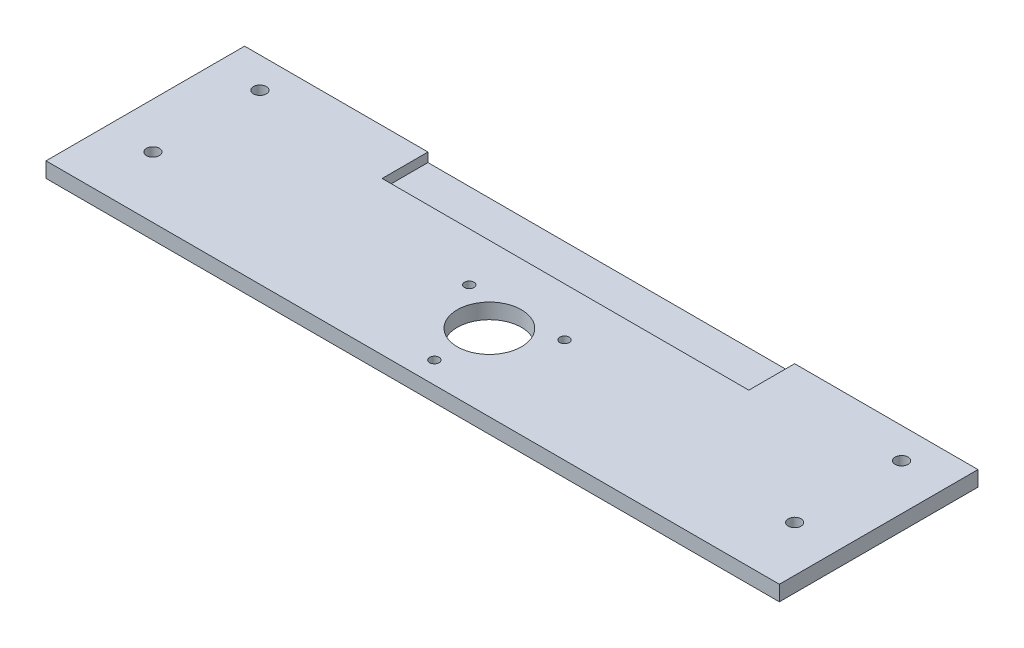
SolidWorks part; units mm, degrees
material "Thornel Mat VMA"
ref_plane "前视基准面" through (0, 0, 0) normal (0, 0, 1) x (1, 0, 0)
ref_plane "上视基准面" through (0, 0, 0) normal (0, 1, 0) x (1, 0, 0)
ref_plane "右视基准面" through (0, 0, 0) normal (1, 0, 0) x (0, 0, -1)
sketch "草图1" plane through (0, 0, 0) normal (0, 1, 0) x (1, 0, 0)
  line L0 (-105, 57.5) -> (-105, -7.5) construction
  line L1 (-120, -7.5) -> (120, -7.5)
  line L2 (-120, -7.5) -> (-120, 57.5)
  line L3 (-120, 57.5) -> (120, 57.5)
  line L4 (120, -7.5) -> (120, 57.5)
  line L5 (-120, -7.5) -> (120, 57.5) construction
  line L6 (-120, 57.5) -> (120, -7.5) construction
  line L7 (0, 57.5) -> (0, -7.5) construction
  line L8 (0, -57.5) -> (0, -7.5) construction
  line L9 (-60, -7.5) -> (20, -7.5)
  circle A0 centre (-105, 47.5) radius 2.1
  circle A1 centre (-105, 12.5) radius 2.1
  circle A2 centre (105, 12.5) radius 2.1
  circle A3 centre (105, 47.5) radius 2.1
  point P0 (0, 25)
  dimension "D1" = 65
  dimension "D2" = 240
  dimension "D3" = 15
  dimension "D4" = 35
  dimension "D5" = 20
extrude "凸台-拉伸1" add sketch "草图1" along normal blind 5 contours L1 L4 L3 L2 A2 A1 A0 A3
sketch "草图2" plane through (0, 5, 0) normal (0, 1, 0) x (1, 0, 0)
  line L0 (0, 57.5) -> (0, -7.5) construction
  line L1 (-120, 57.5) -> (120, 57.5) construction
  line L2 (-120, -7.5) -> (120, -7.5) construction
  line L3 (-60, 57.5) -> (-60, 42.5)
  line L4 (-60, 42.5) -> (60, 42.5)
  line L5 (60, 57.5) -> (60, 42.5)
  line L6 (-60, 57.5) -> (60, 57.5)
  point P10 (0, 42.5)
  dimension "D1" = 15
  dimension "D2" = 60
extrude "切除-拉伸1" cut sketch "草图2" against normal blind 3
fillet "圆角1" [suppressed] radius 5
sketch "草图3" plane through (0, 5, 0) normal (0, 1, 0) x (1, 0, 0)
  line L0 (-55, 42.5) -> (55, 42.5) construction
  line L1 (-55, 42.5) -> (55, 42.5)
  line L2 (0, 42.5) -> (0, -7.3132) construction
  circle A0 centre (0, 17.5934) radius 10.5
  circle A1 centre (0, -0.4066) radius 1.55
  circle A2 centre (-15.5885, 26.5934) radius 1.55
  circle A3 centre (15.5885, 26.5934) radius 1.55
  point P16 (0, 17.5934)
  dimension "D1" = 3
extrude "切除-拉伸2" cut sketch "草图3" against normal blind 32 contours L2 A0 | A0 L2 | A3 | L2 A1 | A1 L2 | A2
sketch "草图4" plane through (0, 5, 0) normal (0, 1, 0) x (1, 0, 0)
  line L0 (22.5, 17.5934) -> (-22.5, 17.5934) construction
  circle A0 centre (0, 17.5934) radius 10.5 construction
  circle A1 centre (0, 17.5934) radius 10.5 construction
  circle A2 centre (-22.5, 17.5934) radius 3.05
  circle A3 centre (22.5, 17.5934) radius 3.05
  point P5 (0, 17.5934)
  dimension "D1" = 22.5
extrude "切除-拉伸3" [suppressed] cut sketch "草图4" against normal blind 10
